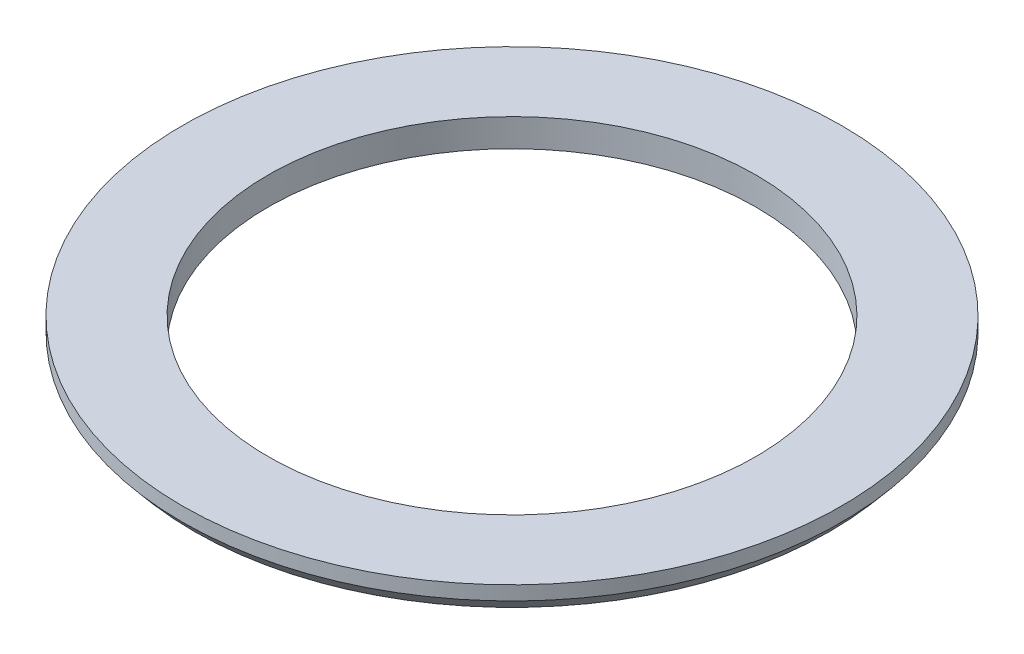
SolidWorks part; units mm, degrees
material "1023 Karbon Çeliği Levha (SS)"
ref_plane "Ön Düzlem" through (0, 0, 0) normal (0, 0, 1) x (1, 0, 0)
ref_plane "Üst Düzlem" through (0, 0, 0) normal (0, 1, 0) x (1, 0, 0)
ref_plane "Sağ Düzlem" through (0, 0, 0) normal (1, 0, 0) x (0, 0, -1)
sketch "Çizim1" plane through (0, 0, 0) normal (0, 0, 1) x (1, 0, 0)
  line L0 (0, 0) -> (12.76, 0) construction
  line L1 (12.76, 0) -> (16.6282, 0.0004)
  line L2 (16.6282, 0.0004) -> (17.2389, 0.7239)
  line L3 (17.2389, 0.7239) -> (17.2388, 1.4572)
  line L4 (17.2388, 1.4572) -> (12.7599, 1.4568)
  line L5 (12.7599, 1.4568) -> (12.76, 0)
  line L6 (0, 0) -> (0, 3.267) construction
revolve "Döndür1" add sketch "Çizim1" angle 360 about L6
